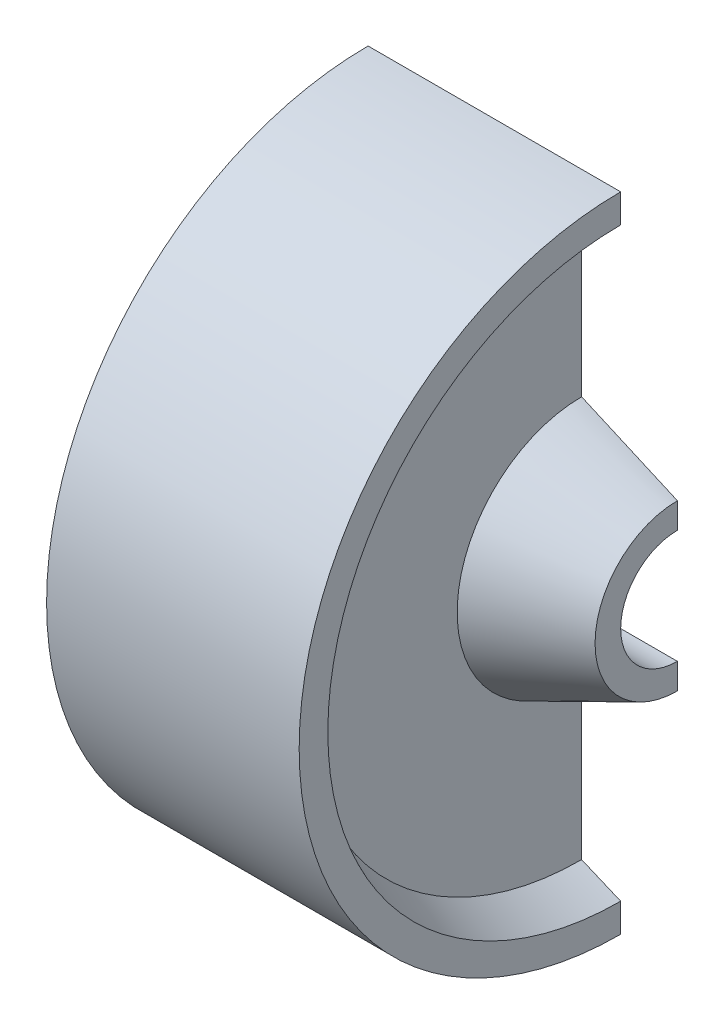
SolidWorks part; units mm, degrees
ref_plane "前视基准面" through (0, 0, 0) normal (0, 0, 1) x (1, 0, 0)
ref_plane "上视基准面" through (0, 0, 0) normal (0, 1, 0) x (1, 0, 0)
ref_plane "右视基准面" through (0, 0, 0) normal (1, 0, 0) x (0, 0, -1)
sketch "草图1" plane through (0, 0, 0) normal (0, 0, 1) x (1, 0, 0)
  line L0 (0, 0) -> (38.8386, 0) construction
  line L1 (0, 0) -> (0, 32.8475) construction
  line L2 (-61.9765, 19.2127) -> (61.9765, 19.2127)
  line L3 (61.9765, 19.2127) -> (61.9765, 27.8894)
  line L4 (61.9765, 27.8894) -> (29.5421, 42.144)
  line L5 (29.5421, 42.144) -> (29.5421, 93.5845)
  line L6 (29.5421, 93.5845) -> (42.7638, 99.1623)
  line L7 (42.7638, 99.1623) -> (42.7638, 108.872)
  line L8 (42.7638, 108.872) -> (-42.7638, 108.872)
  line L9 (-42.7638, 99.1623) -> (-42.7638, 108.872)
  line L10 (-29.5421, 93.5845) -> (-42.7638, 99.1623)
  line L11 (-29.5421, 42.144) -> (-29.5421, 93.5845)
  line L12 (-61.9765, 27.8894) -> (-29.5421, 42.144)
  line L13 (-61.9765, 19.2127) -> (-61.9765, 27.8894)
  point P14 (0, 108.872)
  point P19 (0, 19.2127)
revolve "旋转1" add sketch "草图1" angle 180 about L0
